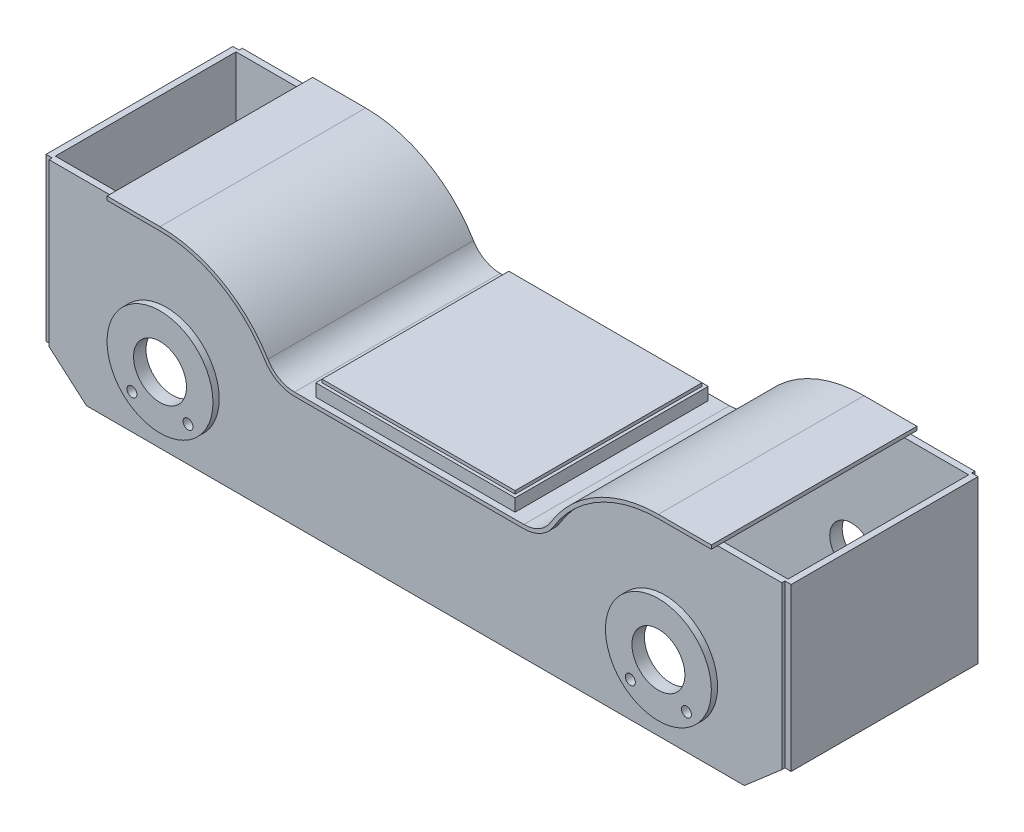
SolidWorks part; units mm, degrees
ref_plane "前视基准面" through (0, 0, 0) normal (0, 0, 1) x (1, 0, 0)
ref_plane "上视基准面" through (0, 0, 0) normal (0, 1, 0) x (1, 0, 0)
ref_plane "右视基准面" through (0, 0, 0) normal (1, 0, 0) x (0, 0, -1)
sketch "草图1" plane through (0, 0, 0) normal (0, 0, 1) x (1, 0, 0)
  line L0 (0, 0) -> (0, 190)
  line L1 (0, 0) -> (528, 0)
  line L2 (0, 190) -> (184, 190)
  line L3 (528, 0) -> (588, 52)
  line L4 (588, 52) -> (588, 312)
  line L5 (588, 312) -> (400, 312)
  circle A0 centre (400, 116) radius 35
  arc A1 (231.9594, 217.0882) -> (400, 312) centre (400, 115.7869) cw
  arc A2 (184, 190) -> (231.9594, 217.0882) centre (184, 246) ccw
  circle A3 centre (355, 66) radius 8
  circle A4 centre (445, 66) radius 8
  dimension "D7" = 70
  dimension "D10" = 56
  dimension "D11" = 16
  dimension "D1" = 528
  dimension "D2" = 190
  dimension "D3" = 184
  dimension "D4" = 588
  dimension "D5" = 260
  dimension "D6" = 312
  dimension "D8" = 400
  dimension "D9" = 196
  dimension "D12" = 45
  dimension "D13" = 90
  dimension "D14" = 50
extrude "凸台-拉伸1" add sketch "草图1" along normal blind 310
mirror "镜向1" about plane through (0, 0, 0) normal (1, 0, 0) of "凸台-拉伸1"
sketch "草图2" plane through (0, 0, 0) normal (0, -1, 0) x (-1, 0, 0)
  line L0 (528, -310) -> (-528, -310) construction
  line L1 (588, -300) -> (-588, -300)
  line L2 (588, -300) -> (588, -10)
  line L3 (588, -10) -> (-588, -10)
  line L4 (-588, -300) -> (-588, -10)
  line L5 (528, 0) -> (-528, 0) construction
  line L6 (-588, -310) -> (-588, 0) construction
  line L7 (588, -310) -> (588, 0) construction
  dimension "D1" = 10
  dimension "D2" = 10
extrude "切除-拉伸1" cut sketch "草图2" against normal through all
ref_plane "基准面1" through (0, 0, 320) normal (0, 0, 1) x (1, 0, 0)
sketch "草图3" plane through (0, 0, 320) normal (0, 0, 1) x (1, 0, 0)
  line L0 (-184, 190) -> (184, 190)
  line L1 (400, 312) -> (485, 312)
  line L2 (588, 312) -> (400, 312) construction
  line L3 (-400, 312) -> (-485, 312)
  line L4 (-588, 312) -> (-400, 312) construction
  line L5 (0, -1000) -> (0, 49000) construction
  line L6 (-485, 312) -> (-485, 318)
  line L7 (-485, 318) -> (-400, 318)
  line L8 (485, 312) -> (485, 318)
  line L9 (485, 318) -> (400, 318)
  line L10 (184, 246) -> (400, 115.7869) construction
  line L11 (-400, 115.7869) -> (-184, 246) construction
  line L12 (-184, 196) -> (184, 196)
  arc A0 (400, 312) -> (231.9594, 217.0882) centre (400, 115.7869) ccw
  arc A1 (184, 190) -> (231.9594, 217.0882) centre (184, 246) ccw
  arc A2 (-400, 312) -> (-231.9594, 217.0882) centre (-400, 115.7869) cw
  arc A3 (-231.9594, 217.0882) -> (-400, 312) centre (-400, 115.7869) ccw construction
  arc A4 (-231.9594, 217.0882) -> (-184, 190) centre (-184, 246) ccw
  arc A5 (-400, 318) -> (-226.8209, 220.1859) centre (-400, 115.7869) cw
  arc A6 (-226.8209, 220.1859) -> (-184, 196) centre (-184, 246) ccw
  arc A7 (184, 196) -> (226.8209, 220.1859) centre (184, 246) ccw
  arc A8 (400, 318) -> (226.8209, 220.1859) centre (400, 115.7869) ccw
  dimension "D1" = 6
  dimension "D2" = 970
  dimension "D3" = 6
  dimension "D4" = 6
  dimension "D5" = 6
extrude "凸台-拉伸2" add sketch "草图3" against normal blind 330 separate body
sketch "草图4" plane through (0, 0, 310) normal (0, 0, 1) x (1, 0, 0)
  circle A0 centre (-400, 116) radius 42.5
  circle A1 centre (400, 116) radius 42.5
  dimension "D1" = 85
  dimension "D2" = 85
extrude "切除-拉伸2" cut sketch "草图4" against normal blind 10
sketch "草图5" plane through (0, 0, 310) normal (0, 0, 1) x (1, 0, 0)
  circle A0 centre (-400, 116) radius 42.5
  circle A1 centre (-355, 66) radius 8
  circle A2 centre (-445, 66) radius 8
  circle A3 centre (-445, 66) radius 8 construction
  circle A4 centre (-355, 66) radius 8 construction
  circle A5 centre (-400, 116) radius 42.5 construction
  circle A6 centre (355, 66) radius 8
  circle A7 centre (445, 66) radius 8
  circle A8 centre (400, 116) radius 42.5
  circle A9 centre (400, 116) radius 42.5 construction
  circle A10 centre (355, 66) radius 8 construction
  circle A11 centre (445, 66) radius 8 construction
  circle A12 centre (-400, 116) radius 85
  circle A13 centre (400, 116) radius 85
  dimension "D1" = 170
  dimension "D2" = 170
extrude "凸台-拉伸3" add sketch "草图5" along normal blind 10
sketch "草图6" plane through (0, 0, 0) normal (0, 0, -1) x (-1, 0, 0)
  circle A0 centre (-355, 66) radius 8
  circle A1 centre (-445, 66) radius 8
  circle A2 centre (-400, 116) radius 85
  circle A3 centre (-400, 116) radius 35
  circle A4 centre (-400, 116) radius 35 construction
  circle A5 centre (-445, 66) radius 8 construction
  circle A6 centre (-355, 66) radius 8 construction
  circle A7 centre (400, 116) radius 85
  circle A8 centre (445, 66) radius 8
  circle A9 centre (355, 66) radius 8
  circle A10 centre (400, 116) radius 35
  circle A11 centre (400, 116) radius 35 construction
  circle A12 centre (355, 66) radius 8 construction
  circle A13 centre (445, 66) radius 8 construction
  dimension "D1" = 170
  dimension "D2" = 170
extrude "凸台-拉伸4" add sketch "草图6" along normal blind 10
sketch "草图7" plane through (0, 190, 0) normal (0, -1, 0) x (-1, 0, 0)
  line L0 (0, -1000) -> (0, 49000) construction
  line L1 (-184, -300) -> (184, -300) construction
  line L2 (-100, -300) -> (-110, -300)
  line L3 (-100, -300) -> (-100, -10)
  line L4 (-100, -10) -> (-110, -10)
  line L5 (-110, -300) -> (-110, -10)
  line L6 (184, -10) -> (-184, -10) construction
  line L7 (528, -10) -> (-528, -10) construction
  line L8 (-150, -300) -> (-160, -300)
  line L9 (-150, -300) -> (-150, -10)
  line L10 (-150, -10) -> (-160, -10)
  line L11 (-160, -300) -> (-160, -10)
  line L13 (110, -300) -> (100, -300)
  line L14 (110, -300) -> (110, -10)
  line L15 (110, -10) -> (100, -10)
  line L16 (100, -300) -> (100, -10)
  line L17 (160, -300) -> (150, -300)
  line L18 (160, -300) -> (160, -10)
  line L19 (160, -10) -> (150, -10)
  line L20 (150, -300) -> (150, -10)
  dimension "D1" = 10
  dimension "D2" = 220
  dimension "D3" = 320
extrude "凸台-拉伸5" add sketch "草图7" along normal blind 184
sketch "草图8" plane through (0, 0, 0) normal (0, -1, 0) x (1, 0, 0)
  line L0 (528, 300) -> (-528, 300) construction
  line L1 (-210, 300) -> (210, 300)
  line L2 (-210, 300) -> (-210, 10)
  line L3 (-210, 10) -> (210, 10)
  line L4 (210, 300) -> (210, 10)
  line L5 (400, 10) -> (231.9594, 10) construction
  line L6 (0, -1000) -> (0, 49000) construction
  dimension "D1" = 420
extrude "凸台-拉伸6" add sketch "草图8" against normal blind 6
sketch "草图9" plane through (0, 312, 0) normal (0, 1, 0) x (1, 0, 0)
  line L0 (-412, -5) -> (49588, -5) construction
  line L2 (588, -10) -> (588, 0) construction
  line L3 (-412, -305) -> (49588, -305) construction
  line L4 (588, -310) -> (588, -300) construction
  line L5 (-588, -10) -> (-588, 0) construction
  line L6 (588, -5) -> (598, -5)
  line L7 (588, -5) -> (588, -305)
  line L8 (588, -305) -> (598, -305)
  line L9 (598, -5) -> (598, -305)
  line L10 (-588, -5) -> (-598, -5)
  line L11 (-588, -5) -> (-588, -305)
  line L12 (-588, -305) -> (-598, -305)
  line L13 (-598, -5) -> (-598, -305)
  point P8 (588, -5)
  point P13 (588, -305)
  dimension "D1" = 10
  dimension "D2" = 10
extrude "凸台-拉伸7" add sketch "草图9" against normal blind 260
sketch "草图10" plane through (0, 196, 0) normal (0, 1, 0) x (1, 0, 0)
  line L0 (-1184, -155) -> (48816, -155) construction
  line L1 (-184, 10) -> (-184, -320) construction
  line L2 (0, -1000) -> (0, 49000) construction
  line L4 (-160, 0) -> (160, 0)
  line L5 (-160, 0) -> (-160, -310)
  line L6 (-160, -310) -> (160, -310)
  line L7 (160, 0) -> (160, -310)
  point P5 (-184, -155)
  dimension "D1" = 320
  dimension "D2" = 310
extrude "凸台-拉伸8" add sketch "草图10" along normal blind 20
sketch "草图11" plane through (0, 216, 0) normal (0, 1, 0) x (1, 0, 0)
  line L0 (160, -310) -> (160, 0) construction
  line L1 (-155, -5) -> (155, -5)
  line L2 (-155, -5) -> (-155, -305)
  line L3 (-155, -305) -> (155, -305)
  line L4 (155, -5) -> (155, -305)
  line L5 (-160, 0) -> (-160, -310) construction
  line L6 (-160, -310) -> (160, -310) construction
  line L7 (160, 0) -> (-160, 0) construction
  dimension "D1" = 5
  dimension "D2" = 5
  dimension "D3" = 5
  dimension "D4" = 5
extrude "凸台-拉伸9" add sketch "草图11" along normal blind 5
